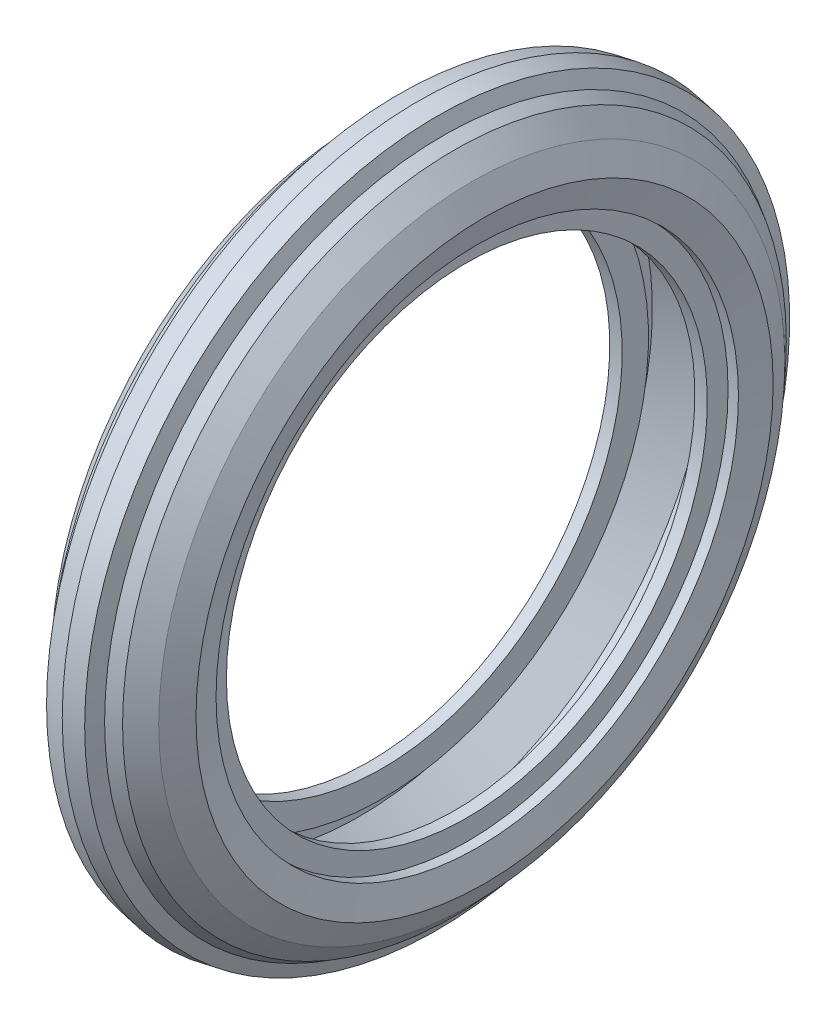
SolidWorks part; units mm, degrees
ref_plane "Front Plane" through (0, 0, 0) normal (0, 0, 1) x (1, 0, 0)
ref_plane "Top Plane" through (0, 0, 0) normal (0, 1, 0) x (1, 0, 0)
ref_plane "Right Plane" through (0, 0, 0) normal (1, 0, 0) x (0, 0, -1)
sketch "Front" plane through (0, 0, 0) normal (0, 0, 1) x (1, 0, 0)
  line L0 (0, 0) -> (0, 6962.2876) construction
  line L1 (0, 0) -> (6962.2876, 0) construction
  line L2 (0, 47.7) -> (4.0477, 46.5794)
  line L3 (4.0477, 46.5794) -> (8.491, 42.4)
  line L4 (8.491, 42.4) -> (8.491, 40.4)
  line L5 (8.491, 40.4) -> (5.2584, 38.6)
  line L6 (5.2584, 38.6) -> (5.2584, 34.8)
  line L7 (5.2584, 34.8) -> (7.0584, 34.8)
  line L8 (7.0584, 34.8) -> (7.0584, 37.8)
  line L9 (7.0584, 37.8) -> (8.5584, 37.8)
  line L10 (8.5584, 37.8) -> (9.6193, 41.7603)
  line L11 (9.6193, 41.7603) -> (7.7605, 45.3022)
  line L12 (7.7605, 45.3022) -> (5.2584, 48.0279)
  line L13 (5.2584, 48.0279) -> (3.6193, 48.9888)
  line L14 (3.6193, 48.9888) -> (2.7573, 51.0129)
  line L15 (2.7573, 51.0129) -> (0, 51.5)
  line L16 (-2.7573, 51.0129) -> (0, 51.5)
  line L17 (-3.6193, 48.9888) -> (-2.7573, 51.0129)
  line L18 (-5.2584, 48.0279) -> (-3.6193, 48.9888)
  line L19 (-7.7605, 45.3022) -> (-5.2584, 48.0279)
  line L20 (-9.6193, 41.7603) -> (-7.7605, 45.3022)
  line L21 (-8.5584, 37.8) -> (-9.6193, 41.7603)
  line L22 (-7.0584, 37.8) -> (-8.5584, 37.8)
  line L23 (-7.0584, 34.8) -> (-7.0584, 37.8)
  line L24 (-5.2584, 34.8) -> (-7.0584, 34.8)
  line L25 (-5.2584, 38.6) -> (-5.2584, 34.8)
  line L26 (-8.491, 40.4) -> (-5.2584, 38.6)
  line L27 (-8.491, 42.4) -> (-8.491, 40.4)
  line L28 (-4.0477, 46.5794) -> (-8.491, 42.4)
  line L29 (0, 47.7) -> (-4.0477, 46.5794)
  point P7 (0, 16.0814)
  point P21 (0, 0)
  point P22 (4.2084, 10.8283)
  point P23 (0, 11.2643)
  point P24 (2.497, 13.7973)
  point P25 (2.497, 13.7973)
  point P26 (0, 14.2138)
  point P27 (4.2084, 10.1016)
  point P28 (0, 0)
  point P29 (0, 10.3923)
  point P30 (4.2084, 10.1743)
  point P31 (0, 14.171)
  point P32 (4.7373, 7.15)
  point P33 (8.8256, 5.8897)
  point P34 (8.8256, 6.5997)
  point P35 (9.96, 10.8854)
  point P36 (9.6392, 11)
  point P37 (0, 0)
  point P38 (3.5143, 14.8921)
  point P39 (5.9189, 17.4994)
  point P40 (3.5143, 18.394)
  point P41 (0, 0)
  point P42 (0, 0)
  point P43 (0, 0)
  point P44 (3.3069, 18.394)
  point P45 (3.5143, 14.9451)
  point P46 (3.9122, 15.0217)
  point P47 (4.0477, 15.5838)
  point P48 (3.2942, 17.8838)
  point P49 (5.2584, 17.0323)
  dimension "D1" = 1.8
  dimension "D2" = 4.2
  dimension "D3" = 6.1
  dimension "D4" = 2
  dimension "D5" = 3.7
  dimension "D6" = 3.8
  dimension "D7" = 3
  dimension "D8" = 1.5
  dimension "D9" = 4.1
  dimension "D10" = 4
  dimension "D11" = 3.7
  dimension "D12" = 1.9
  dimension "D13" = 2.2
  dimension "D14" = 2.8
  dimension "D15" = 3.8
  dimension "D16" = 12.9
  dimension "D17" = 16.2129
  dimension "D18" = 7.6
  dimension "D19" = 5.6
  dimension "D20" = 69.6
sketch "Top" plane through (0, 0, 0) normal (0, 1, 0) x (1, 0, 0)
  line L0 (0, 0) -> (0, 50000) construction
  line L1 (0, 0) -> (50000, 0) construction
sketch "Right" plane through (0, 0, 0) normal (1, 0, 0) x (0, 0, -1)
  line L0 (0, 0) -> (0, 50000) construction
  line L1 (0, 0) -> (50000, 0) construction
revolve "Revolve1" add sketch "Front" angle 360 about L1
